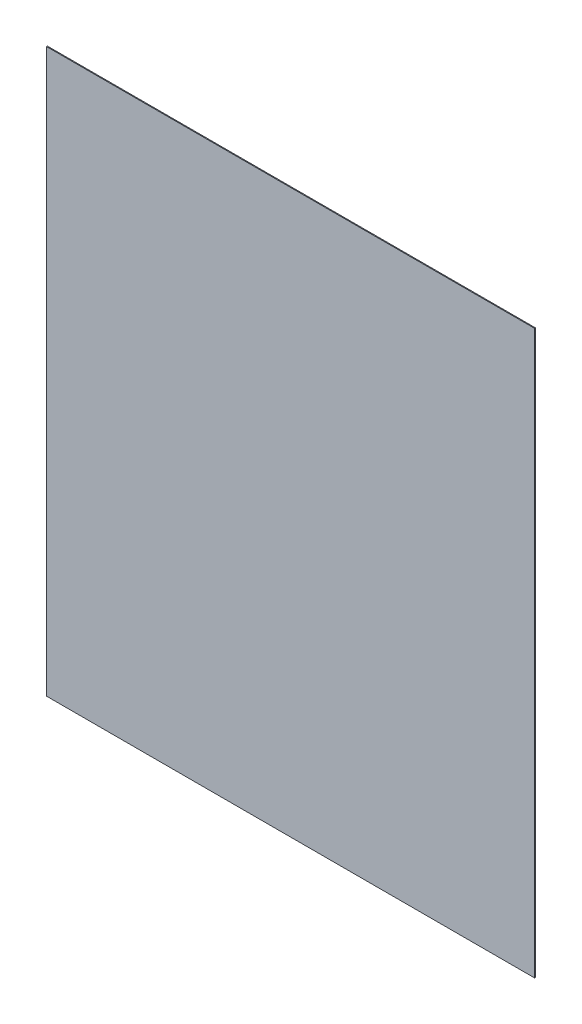
SolidWorks part; units mm, degrees
ref_plane "Alzado" through (0, 0, 0) normal (0, 0, 1) x (1, 0, 0)
ref_plane "Planta" through (0, 0, 0) normal (0, 1, 0) x (1, 0, 0)
ref_plane "Vista lateral" through (0, 0, 0) normal (1, 0, 0) x (0, 0, -1)
sketch "Croquis1" plane through (0, 0, 0) normal (0, 0, 1) x (1, 0, 0)
  line L1 (-250, 288.1) -> (250, 288.1)
  line L2 (-250, 288.1) -> (-250, -288.1)
  line L3 (-250, -288.1) -> (250, -288.1)
  line L4 (250, 288.1) -> (250, -288.1)
  line L5 (-250, 288.1) -> (250, -288.1) construction
  line L6 (-250, -288.1) -> (250, 288.1) construction
  point P0 (0, 0)
  dimension "D1" = 500
  dimension "D2" = 576.2
extrude "Saliente-Extruir1" add sketch "Croquis1" along normal blind 0.9
